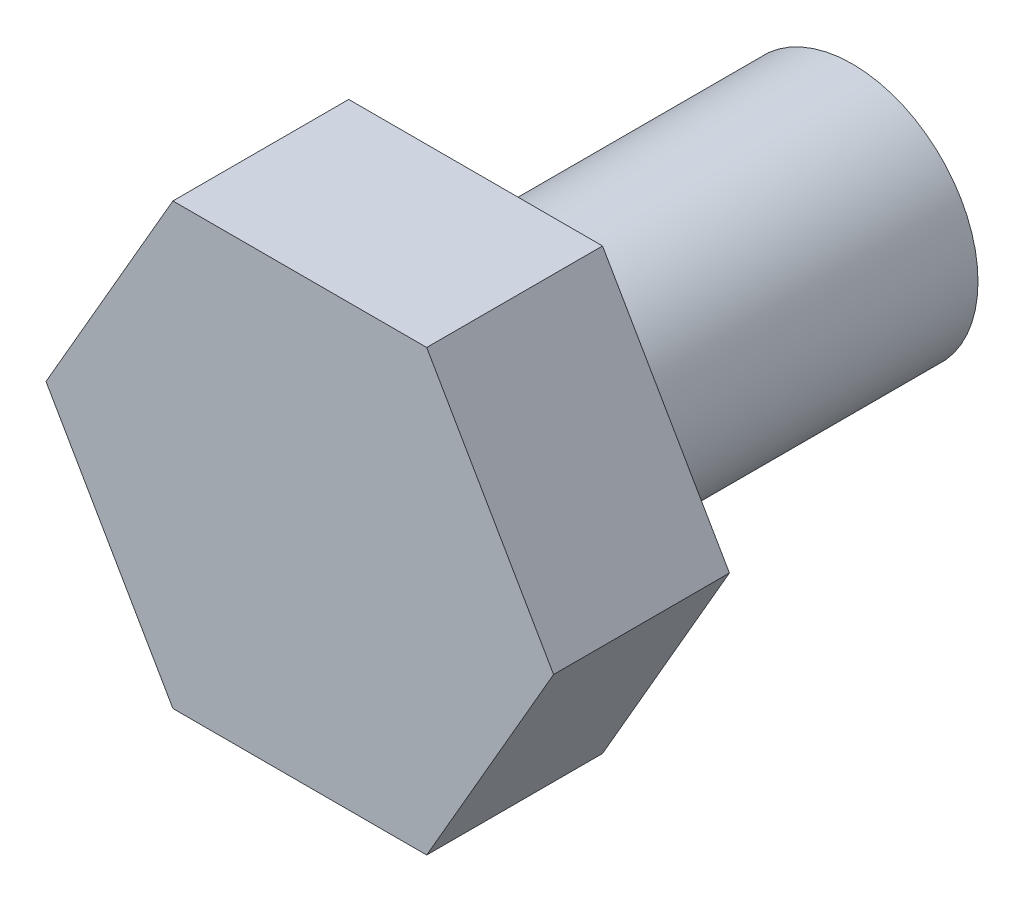
SolidWorks part; units mm, degrees
material "AISI 304"
ref_plane "Front Plane" through (0, 0, 0) normal (0, 0, 1) x (1, 0, 0)
ref_plane "Top Plane" through (0, 0, 0) normal (0, 1, 0) x (1, 0, 0)
ref_plane "Right Plane" through (0, 0, 0) normal (1, 0, 0) x (0, 0, -1)
sketch "Sketch1" plane through (0, 0, 0) normal (0, 0, 1) x (1, 0, 0)
  circle A0 centre (0, 0) radius 2
  dimension "D1" = 4
extrude "Extrude1" add sketch "Sketch1" against normal blind 6
cosmetic thread "Cosmetic Thread1" parameters "D1"=6, "D2"=3.22
sketch "Sketch2" plane through (0, 0, 0) normal (0, 0, 1) x (1, 0, 0)
  line L1 (-2.0207, 3.5) -> (-4.0415, 0)
  line L2 (-4.0415, 0) -> (-2.0207, -3.5)
  line L3 (-2.0207, -3.5) -> (2.0207, -3.5)
  line L4 (2.0207, -3.5) -> (4.0415, 0)
  line L5 (4.0415, 0) -> (2.0207, 3.5)
  line L6 (2.0207, 3.5) -> (-2.0207, 3.5)
  circle A0 centre (0, 0) radius 3.5 construction
  dimension "D1" = 7
extrude "Extrude2" add sketch "Sketch2" along normal blind 2.8
